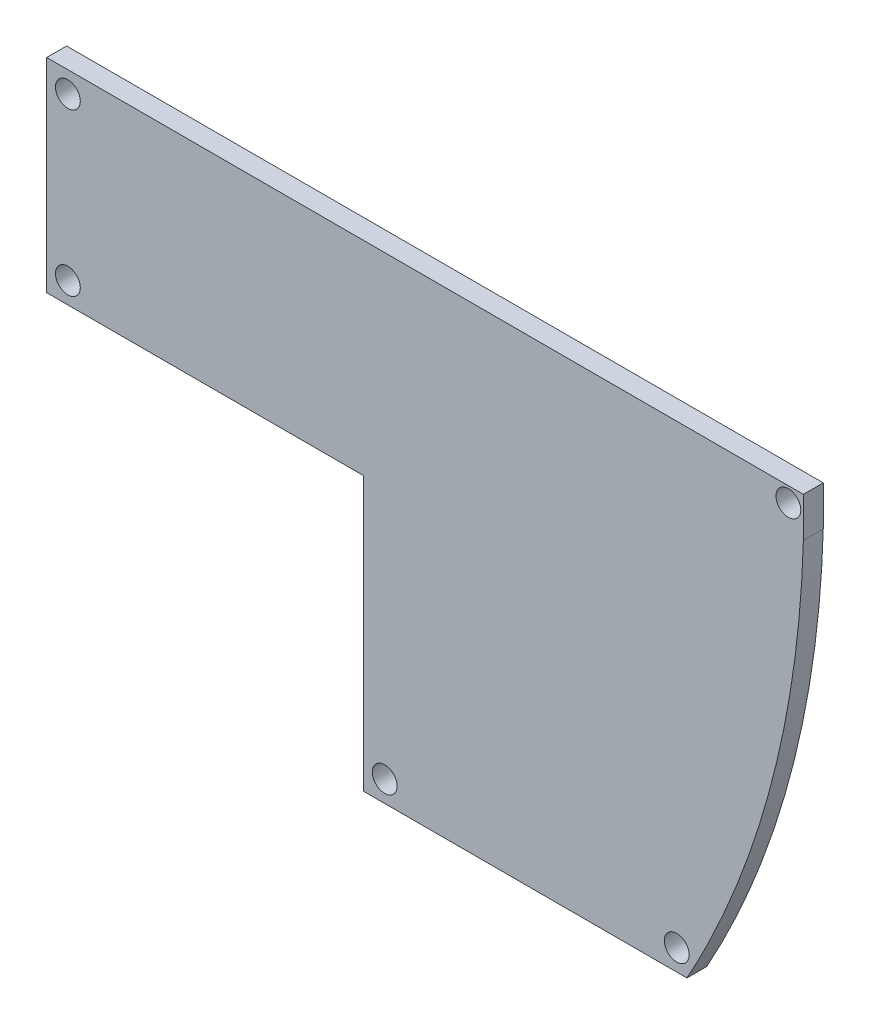
SolidWorks part; units mm, degrees
ref_plane "前视基准面" through (0, 0, 0) normal (0, 0, 1) x (1, 0, 0)
ref_plane "上视基准面" through (0, 0, 0) normal (0, 1, 0) x (1, 0, 0)
ref_plane "右视基准面" through (0, 0, 0) normal (1, 0, 0) x (0, 0, -1)
sketch "草图1" plane through (0, 0, 0) normal (0, 0, 1) x (1, 0, 0)
  line L29 (-87.7, -15.7) -> (-62.2, -15.7)
  line L30 (-87.7, 0.7) -> (-87.7, -15.7)
  line L31 (-26.8, 0.7) -> (-87.7, 0.7)
  line L32 (-26.8, -2.5036) -> (-26.8, 0.7)
  line L33 (-62.2, -37.7) -> (-36.1717, -37.7)
  line L34 (-62.2, -15.7) -> (-62.2, -37.7)
  line L35 (-87.7, -15.7) -> (-62.2, -15.7)
  line L36 (-87.7, 0.7) -> (-87.7, -15.7)
  line L37 (-26.8, 0.7) -> (-87.7, 0.7)
  line L38 (-26.8, -2.5036) -> (-26.8, 0.7)
  line L39 (-62.2, -37.7) -> (-36.1717, -37.7)
  line L40 (-62.2, -15.7) -> (-62.2, -37.7)
  circle A0 centre (-86, -1) radius 1 construction
  circle A1 centre (-86, -1) radius 1
  circle A2 centre (-86, -14) radius 1 construction
  circle A3 centre (-86, -14) radius 1
  circle A4 centre (-28.0081, -0.5081) radius 1 construction
  circle A5 centre (-28.0081, -0.5081) radius 1
  circle A6 centre (-36.995, -36) radius 1 construction
  circle A7 centre (-36.995, -36) radius 1
  circle A8 centre (-60.5, -36) radius 1 construction
  circle A9 centre (-60.5, -36) radius 1
  spline S6 degree 3 poles (874.2585, -2062.2803) (-4735.0341, 1123.8013) (-212.1068, -479.1779) (-31.0869, -26.5332) (-30.1291, -23.6183) (-28.9617, -19.1602) (-28.6187, -17.6649) (-28.0233, -14.6646) (-27.7703, -13.1583) (5.6535, 227.4927) (-1032.5287, 614.4138) (3892.0275, 178.8687) knots -39.161087 -39.161087 -39.161087 -39.161087 0.25 0.25 0.5 0.5 0.625 0.625 0.75 0.75 20.516837 20.516837 20.516837 20.516837 only from (-36.1717, -37.7) to (-26.8, -2.5036)
  spline S7 degree 3 poles (-36.1717, -37.7) (-34.6848, -35.0103) (-33.369, -32.2396) (-31.0869, -26.5332) (-30.1291, -23.6183) (-28.9617, -19.1602) (-28.6187, -17.6649) (-28.0233, -14.6646) (-27.7703, -13.1583) (-27.1402, -8.6216) (-26.8915, -5.5734) (-26.8, -2.5036) knots 0 0 0 0 0.25 0.25 0.5 0.5 0.625 0.625 0.75 0.75 1 1 1 1
  dimension "D1" = 0.3
extrude "凸台-拉伸1" add sketch "草图1" along normal blind 1.6
